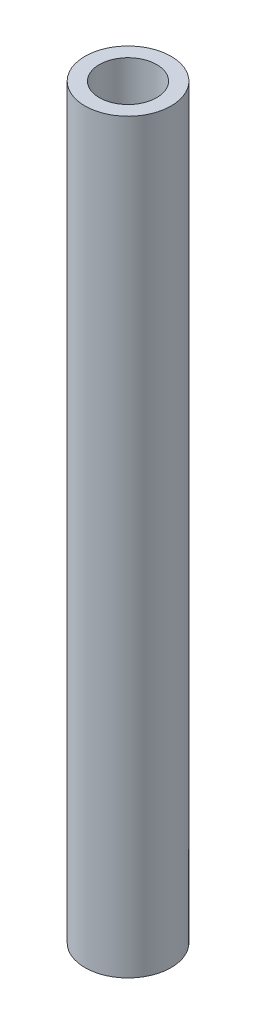
SolidWorks part; units mm, degrees
material "Custom Plastic"
ref_plane "Front Plane" through (0, 0, 0) normal (0, 0, 1) x (1, 0, 0)
ref_plane "Top Plane" through (0, 0, 0) normal (0, 1, 0) x (1, 0, 0)
ref_plane "Right Plane" through (0, 0, 0) normal (1, 0, 0) x (0, 0, -1)
sketch "Sketch1" plane through (0, 0, 0) normal (0, 1, 0) x (1, 0, 0)
  circle A0 centre (0, 0) radius 2
  circle A1 centre (0, 0) radius 3
  dimension "D1" = 4
  dimension "D2" = 6
extrude "Boss-Extrude1" add sketch "Sketch1" along normal blind 52
